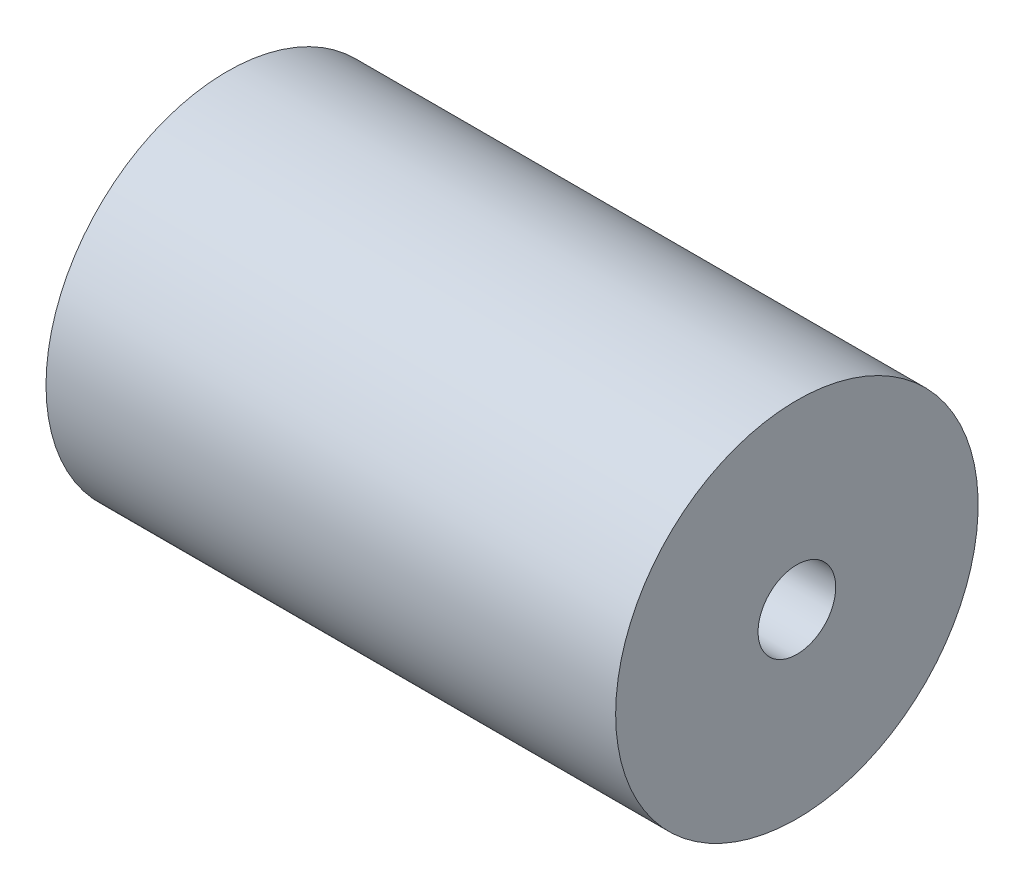
SolidWorks part; units mm, degrees
material "6061 合金"
ref_plane "前视基准面" through (0, 0, 0) normal (0, 0, 1) x (1, 0, 0)
ref_plane "上视基准面" through (0, 0, 0) normal (0, 1, 0) x (1, 0, 0)
ref_plane "右视基准面" through (0, 0, 0) normal (1, 0, 0) x (0, 0, -1)
sketch "草图1" plane through (0, 0, 0) normal (0, 0, 1) x (1, 0, 0)
  line L0 (0, 0) -> (0, 5) construction
  line L1 (0, 0) -> (6.3327, 0) construction
  line L2 (-11, 3) -> (11, 3)
  line L3 (-11, 3) -> (-11, 7)
  line L4 (-11, 7) -> (11, 7)
  line L5 (11, 3) -> (11, 7)
  line L6 (-11, 3) -> (11, 7) construction
  line L7 (-11, 7) -> (11, 3) construction
  dimension "D1" = 6
  dimension "D2" = 14
  dimension "D3" = 22
revolve "旋转1" add sketch "草图1" angle 360 about L1
sketch "草图2" plane through (0, 0, 0) normal (0, 0, 1) x (1, 0, 0)
  line L0 (11, -3) -> (11, 3) construction
  line L1 (11, -3) -> (11, 3) construction
  line L2 (11, 0) -> (-11, 0) construction
  line L3 (-11, 7) -> (-11, -7) construction
  line L5 (11, 3) -> (3.6667, 3)
  line L6 (11, 3) -> (11, 2.2088)
  line L7 (11, 2.2088) -> (3.6667, 2.2088)
  line L8 (3.6667, 3) -> (3.6667, 2.2088)
  dimension "D1" = 22
  dimension "D2" = 4.4175
  dimension "D3" = 7.3333
revolve "旋转2" [suppressed] add sketch "草图2" angle 360 about L2
sketch "草图3" plane through (11, 0, 0) normal (1, 0, 0) x (0, 0, -1)
  circle A0 centre (0, 0) radius 1.5
  circle A1 centre (0, 0) radius 3
extrude "凸台-拉伸1" add sketch "草图3" against normal blind 5
equation "\"D3@草图2\"=\"D1@草图2\"/3"
